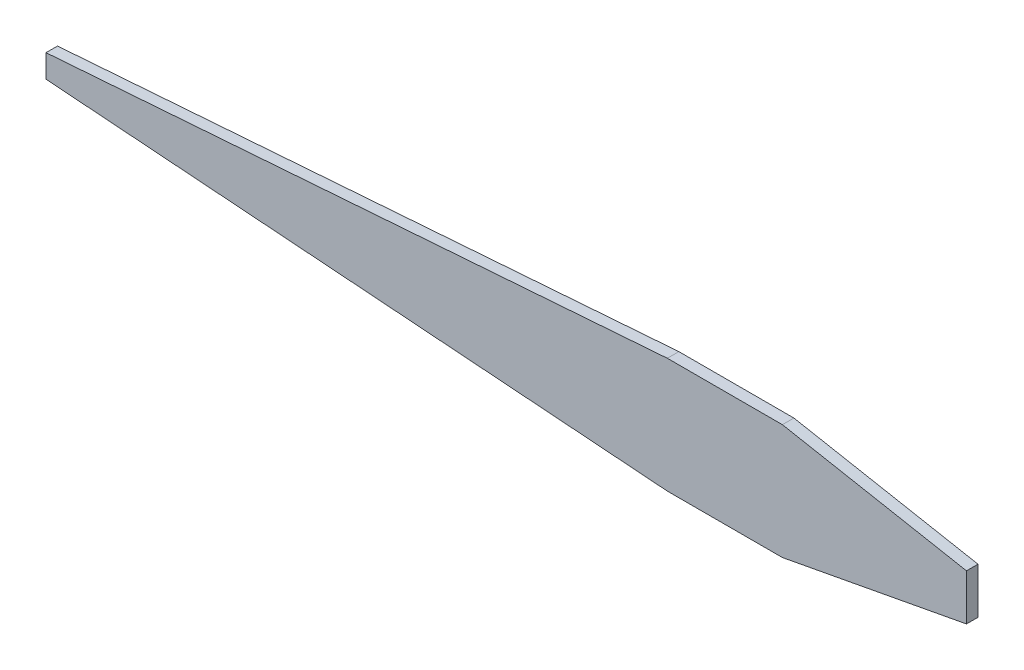
SolidWorks part; units mm, degrees
material "Heavy Pine"
ref_plane "Front Plane" through (0, 0, 0) normal (0, 0, 1) x (1, 0, 0)
ref_plane "Top Plane" through (0, 0, 0) normal (0, 1, 0) x (1, 0, 0)
ref_plane "Right Plane" through (0, 0, 0) normal (1, 0, 0) x (0, 0, -1)
sketch "Sketch1" plane through (0, 0, 0) normal (0, 0, 1) x (1, 0, 0)
  line L0 (200, 20) -> (40, 50)
  line L1 (40, 50) -> (-60, 50)
  line L2 (-60, 50) -> (-600, 10)
  line L3 (-600, 10) -> (-600, -10)
  line L4 (-600, -10) -> (-60, -50)
  line L5 (-60, -50) -> (40, -50)
  line L6 (40, -50) -> (200, -20)
  line L7 (200, -20) -> (200, 20)
  line L8 (0, 0) -> (200, 0) construction
  line L9 (-600, 0) -> (0, 0) construction
  dimension "D1" = 200
  dimension "D2" = 600
  dimension "D3" = 100
  dimension "D4" = 60
  dimension "D5" = 40
  dimension "D6" = 40
  dimension "D7" = 20
extrude "Boss-Extrude1" add sketch "Sketch1" along normal mid plane 10
